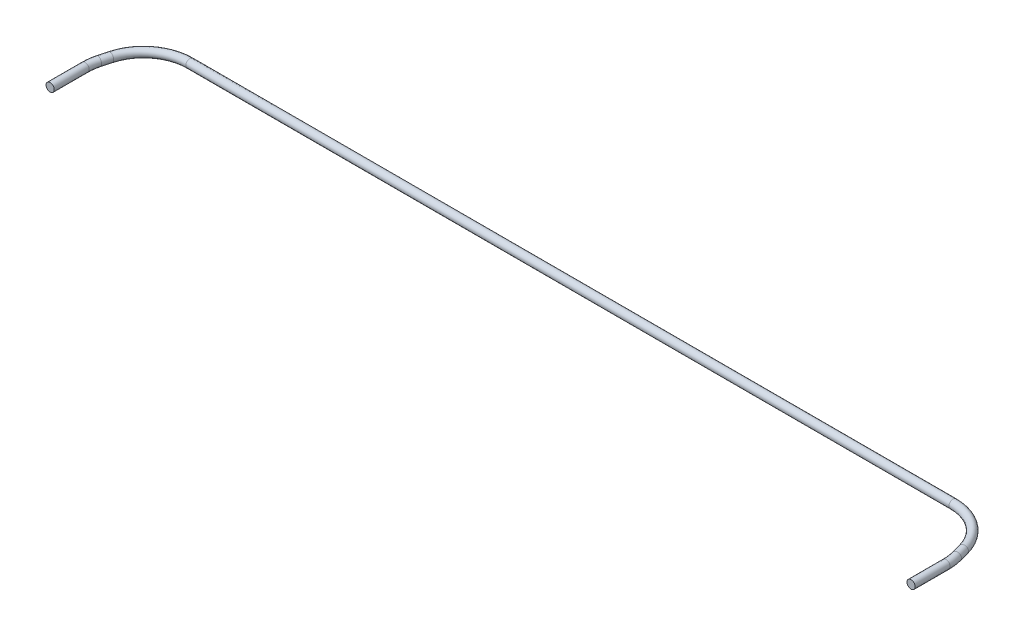
SolidWorks part; units mm, degrees
material "Copper"
ref_plane "Front Plane" through (0, 0, 0) normal (0, 0, 1) x (1, 0, 0)
ref_plane "Top Plane" through (0, 0, 0) normal (0, 1, 0) x (1, 0, 0)
ref_plane "Right Plane" through (0, 0, 0) normal (1, 0, 0) x (0, 0, -1)
ref_plane "Board Plane" through (0, -1.294, 0) normal (0, 1, 0) x (1, 0, 0)
sketch "Sketch1" plane through (0, 0, 0) normal (0, 1, 0) x (1, 0, 0)
  line L0 (0, 78.0606) -> (0, -20.9002) construction
  line L1 (0, -1.4235) -> (0, 1.4235) construction
  line L2 (0, 2.5883) -> (120, 2.5883)
  line L4 (134.0912, -8.2243) -> (134.895, -11.2243)
  line L5 (135.3921, -15) -> (135.3921, -26)
  line L6 (-1.4235, 0) -> (1.4235, 0) construction
  arc A0 (120, 2.5883) -> (134.0912, -8.2243) centre (120, -12) cw
  arc A1 (134.895, -11.2243) -> (135.3921, -15) centre (120.8038, -15) cw
  point P12 (131.194, 2.5883)
  point P15 (135.3921, -13.0794)
  dimension "D4" = 14.5883
  dimension "D1" = 105
  dimension "D2" = 240
  dimension "D3" = 28.5883
  dimension "D6" = 17.5883
  dimension "D5" = 2.5883
sketch "Sketch2" plane through (0, 0, 0) normal (1, 0, 0) x (0, 0, -1)
  circle A0 centre (2.5883, 0) radius 1.2941
  dimension "D1" = 2.5883
sweep "Sweep1" add profiles "Sketch2" path "Sketch1"
mirror "Mirror1" about plane through (0, 0, 0) normal (1, 0, 0) of "Sweep1"
equation "\"Gauge Diameter\"= 0.1019in'10 AWG solid wire"
equation "\"D1@Sketch2\"=\"Gauge Diameter\""
equation "\"D4@Sketch1\"=12.00mm+\"Gauge Diameter\""
equation "\"D6@Sketch1\"=15.00mm+\"Gauge Diameter\""
equation "\"D3@Sketch1\"=26mm+\"Gauge Diameter\""
equation "\"D5@Sketch1\"=\"Gauge Diameter\""
